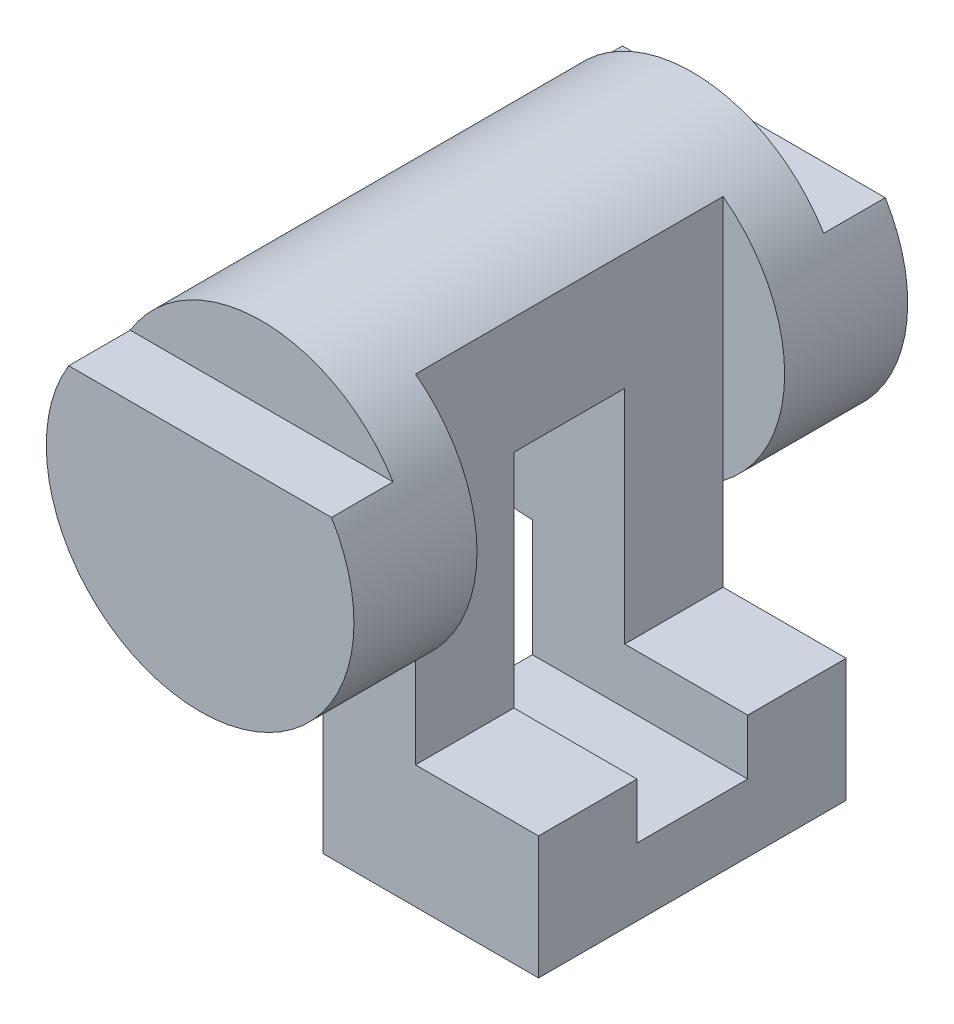
SolidWorks part; units mm, degrees
ref_plane "Alzado" through (0, 0, 0) normal (0, 0, 1) x (1, 0, 0)
ref_plane "Planta" through (0, 0, 0) normal (0, 1, 0) x (1, 0, 0)
ref_plane "Vista lateral" through (0, 0, 0) normal (1, 0, 0) x (0, 0, -1)
sketch "Croquis1" plane through (0, 0, 0) normal (0, 0, 1) x (1, 0, 0)
  line L0 (-15, 10) -> (-15, -20)
  line L1 (-15, -20) -> (20, -20)
  line L2 (20, -20) -> (20, 0)
  line L3 (20, 0) -> (0, 0)
  line L4 (0, 0) -> (0, 15)
  line L5 (-15, 35) -> (-15, -20) construction
  arc A0 (0, 15) -> (-15, 10) centre (-15, 35) ccw
  dimension "D1" = 50
  dimension "D2" = 35
  dimension "D3" = 20
  dimension "D4" = 55
  dimension "D5" = 20
extrude "Saliente-Extruir1" add sketch "Croquis1" along normal mid plane 50
sketch "Croquis2" plane through (0, 0, 0) normal (0, 0, 1) x (1, 0, 0)
  line L5 (-15, -20) -> (20, -20)
  line L6 (20, -20) -> (20, 0)
  line L7 (20, 0) -> (0, 0)
  line L8 (0, 0) -> (0, 15)
  line L9 (-15, 10) -> (-15, -20)
  circle A0 centre (-15, 35) radius 25
  arc A1 (0, 15) -> (-15, 10) centre (-15, 35) ccw
  arc A2 (0, 15) -> (-15, 10) centre (-15, 35) ccw
  dimension "D1" = 0
extrude "Saliente-Extruir2" add sketch "Croquis2" along normal mid plane 90 contours A0
sketch "Croquis3" plane through (20, 0, 0) normal (1, 0, 0) x (0, 0, -1)
  line L0 (-25, 0) -> (-25, 15) construction
  line L1 (-9, -9) -> (9, -9)
  line L2 (-9, -9) -> (-9, 36)
  line L3 (-9, 36) -> (9, 36)
  line L4 (9, -9) -> (9, 36)
  line L6 (-25, 0) -> (25, 0) construction
  line L7 (-45, 60) -> (-45, 10) construction
  line L8 (-45, 48) -> (-35, 48)
  line L9 (-45, 48) -> (-45, 60)
  line L10 (-45, 60) -> (-35, 60)
  line L11 (-35, 48) -> (-35, 60)
  line L12 (45, 60) -> (-45, 60) construction
  line L13 (0, 52.4663) -> (0, -52.4663) construction
  line L14 (45, 60) -> (35, 60)
  line L15 (35, 48) -> (35, 60)
  line L16 (45, 48) -> (35, 48)
  line L17 (45, 48) -> (45, 60)
  point P16 (0, 0)
  point P17 (0, 52.4663)
  dimension "D1" = 18
  dimension "D2" = 45
  dimension "D3" = 16
  dimension "D4" = 9
  dimension "D5" = 10
  dimension "D6" = 12
extrude "Cortar-Extruir1" cut sketch "Croquis3" against normal through all
sketch "Croquis6" plane through (0, 0, 0) normal (0, 1, 0) x (1, 0, 0)
  line L0 (20, -25) -> (0, -25) construction
  line L1 (0, 25) -> (10, 25)
  line L2 (0, 25) -> (0, -25)
  line L3 (0, -25) -> (10, -25)
  line L4 (10, 25) -> (10, -25)
extrude "Cortar-Extruir2" cut sketch "Croquis6" along normal through all
